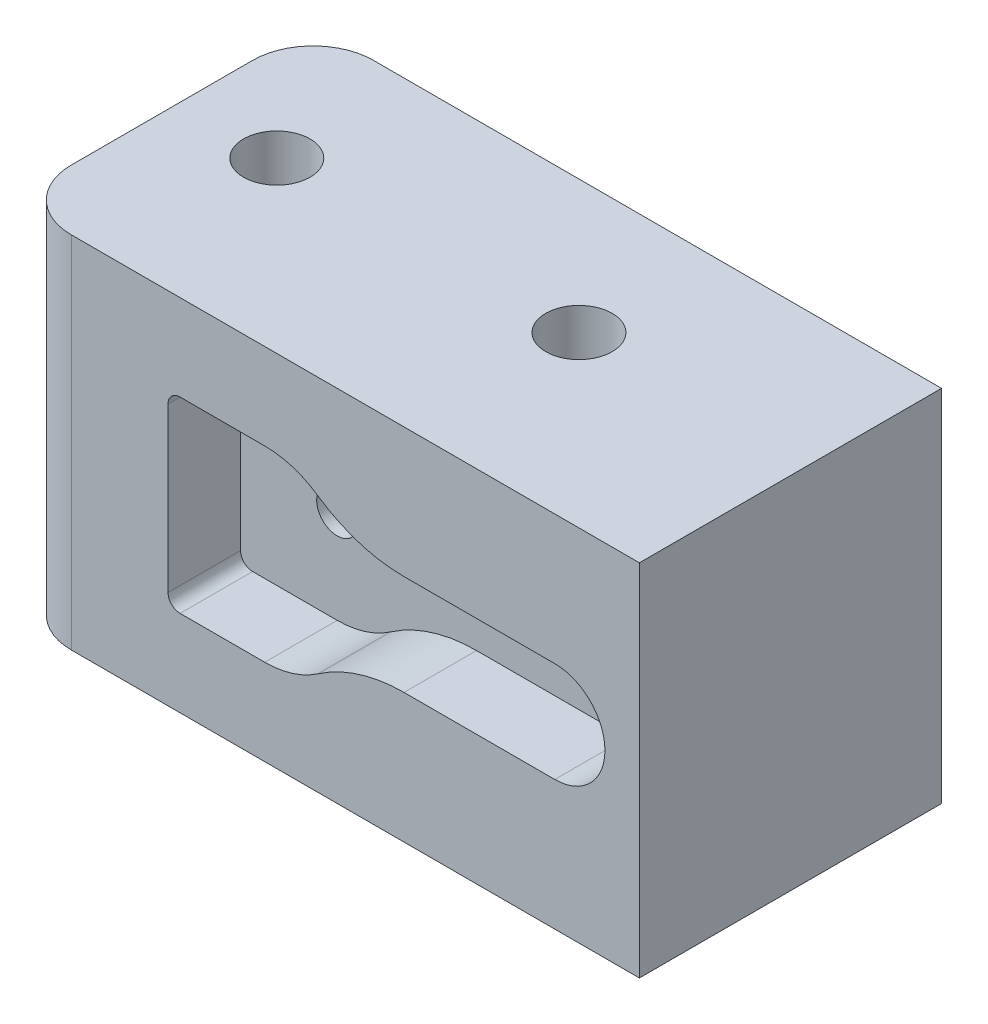
SolidWorks part; units mm, degrees
ref_plane "Front Plane" through (0, 0, 0) normal (0, 0, 1) x (1, 0, 0)
ref_plane "Top Plane" through (0, 0, 0) normal (0, 1, 0) x (1, 0, 0)
ref_plane "Right Plane" through (0, 0, 0) normal (1, 0, 0) x (0, 0, -1)
sketch "Sketch1" plane through (0, 0, 0) normal (0, 1, 0) x (1, 0, 0)
  line L0 (0, -11) -> (0, 11) construction
  line L1 (-26, -12.5) -> (26, -12.5)
  line L2 (-26, -12.5) -> (-26, 12.5)
  line L3 (-26, 12.5) -> (26, 12.5)
  line L4 (26, -12.5) -> (26, 12.5)
  line L5 (-26, -12.5) -> (26, 12.5) construction
  line L6 (-26, 12.5) -> (26, -12.5) construction
  line L7 (-16.5, 0) -> (16.5, 0) construction
  point P0 (0, 0)
  dimension "D1" = 52
  dimension "D2" = 25
extrude "Boss-Extrude1" add sketch "Sketch1" along normal blind 29.75 contours L2 L3 L4 L1
sketch "Sketch2" plane through (0, 0, 12.5) normal (0, 0, 1) x (1, 0, 0)
  line L0 (13.75, 0) -> (-13.75, 0) construction
  line L1 (-26, 29.75) -> (-26, 0) construction
  line L2 (-5, 14.875) -> (19, 14.875) construction
  line L3 (19, 19.025) -> (6.5256, 19.025)
  line L4 (19, 10.725) -> (6.5256, 10.725)
  line L5 (-5, 22.625) -> (-12, 22.625)
  line L6 (-13, 21.625) -> (-13, 8.125)
  line L7 (-12, 7.125) -> (-5, 7.125)
  arc A0 (-0.589, 21.2472) -> (-5, 22.625) centre (-5, 14.875) ccw
  arc A1 (19, 10.725) -> (19, 19.025) centre (19, 14.875) ccw
  arc A2 (-5, 7.125) -> (-0.589, 8.5028) centre (-5, 14.875) ccw
  arc A3 (-12, 7.125) -> (-13, 8.125) centre (-12, 8.125) cw
  arc A4 (-13, 21.625) -> (-12, 22.625) centre (-12, 21.625) cw
  arc A5 (-0.589, 8.5028) -> (6.5256, 10.725) centre (6.5256, -1.775) cw
  arc A6 (-0.589, 21.2472) -> (6.5256, 19.025) centre (6.5256, 31.525) ccw
  dimension "D1" = 7.75
  dimension "D5" = 8.3
  dimension "D6" = 1
  dimension "D7" = 12.5
  dimension "D2" = 14.875
  dimension "D3" = 21
  dimension "D4" = 24
  dimension "D8" = 8
extrude "Cut-Extrude1" cut sketch "Sketch2" against normal blind 6
sketch "Sketch4" plane through (0, 29.75, 0) normal (0, 1, 0) x (1, 0, 0)
  line L0 (7, 1.5) -> (-18, 1.5) construction
  line L1 (-26, -12.5) -> (-26, 12.5) construction
  line L2 (-26, -12.5) -> (26, -12.5) construction
  circle A0 centre (-18, 1.5) radius 2.75
  circle A1 centre (7, 1.5) radius 2.75
  dimension "D1" = 5.5
  dimension "D3" = 25
  dimension "D2" = 8
  dimension "D4" = 14
extrude "Cut-Extrude2" cut sketch "Sketch4" against normal up to next
sketch "Sketch5" plane through (0, 0, 6.5) normal (0, 0, 1) x (1, 0, 0)
  circle A0 centre (-5, 14.875) radius 1.7
  circle A1 centre (19, 14.875) radius 1.7
  arc A2 (19, 10.725) -> (19, 19.025) centre (19, 14.875) ccw construction
  arc A3 (-0.589, 21.2472) -> (-5, 22.625) centre (-5, 14.875) ccw construction
  dimension "D1" = 3.4
extrude "Cut-Extrude3" cut sketch "Sketch5" against normal up to next
fillet "Fillet1" radius 5 2 edges at (-26, 14.875, -12.5) (-26, 14.875, 12.5)
sketch "Sketch6" plane through (0, 0, -12.5) normal (0, 0, -1) x (-1, 0, 0)
  circle A0 centre (-19, 14.875) radius 3.5
  circle A1 centre (5, 14.875) radius 3.5
  dimension "D1" = 7
extrude "Cut-Extrude4" cut sketch "Sketch6" against normal blind 8
